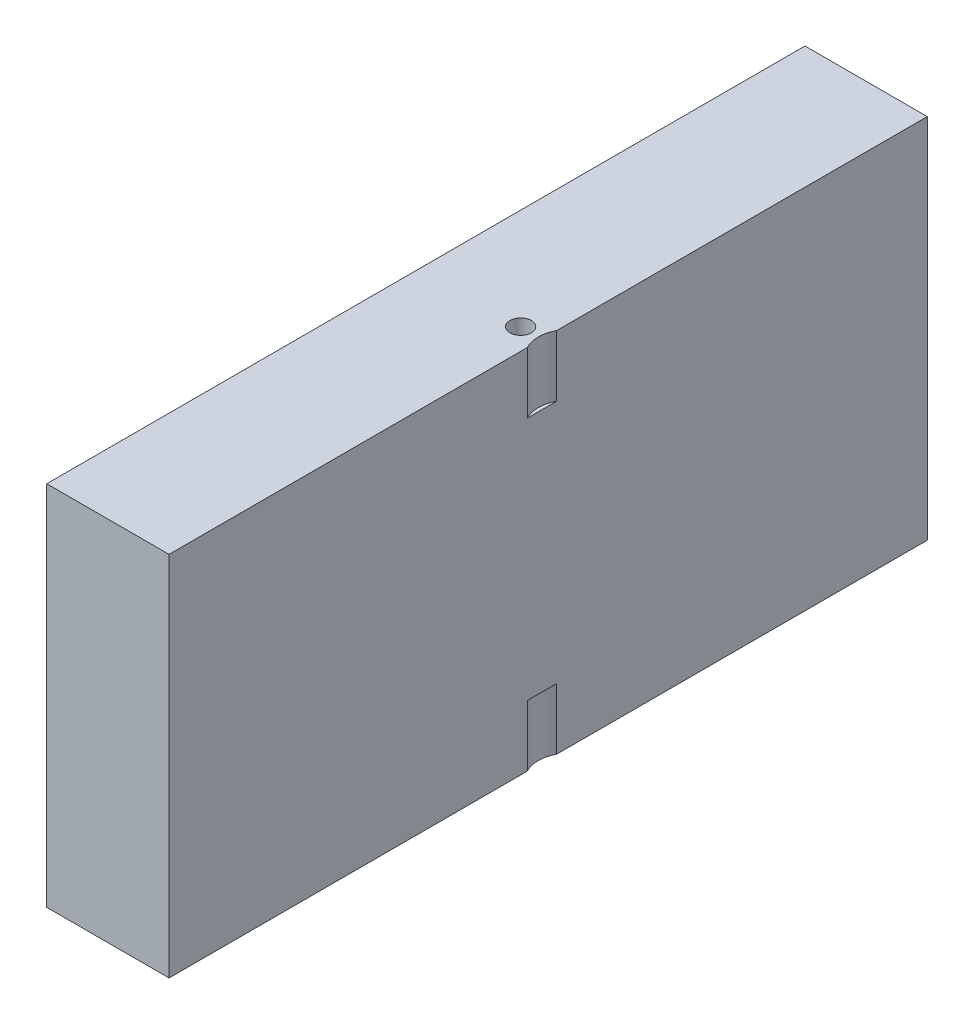
SolidWorks part; units mm, degrees
ref_plane "Front Plane" through (0, 0, 0) normal (0, 0, 1) x (1, 0, 0)
ref_plane "Top Plane" through (0, 0, 0) normal (0, 1, 0) x (1, 0, 0)
ref_plane "Right Plane" through (0, 0, 0) normal (1, 0, 0) x (0, 0, -1)
sketch "Sketch1" plane through (0, 0, 0) normal (0, 0, 1) x (1, 0, 0)
  line L1 (-10, -30) -> (10, -30)
  line L2 (-10, -30) -> (-10, 30)
  line L3 (-10, 30) -> (10, 30)
  line L4 (10, -30) -> (10, 30)
  line L5 (-10, -30) -> (10, 30) construction
  line L6 (-10, 30) -> (10, -30) construction
  point P0 (0, 0)
  dimension "D1" = 60
  dimension "D2" = 20
extrude "Boss-Extrude1" add sketch "Sketch1" along normal mid plane 124
sketch "Sketch2" plane through (0, 30, 0) normal (0, 1, 0) x (1, 0, 0)
  line L0 (-10, -1) -> (14.5, -1) construction
  line L1 (-10, -62) -> (-10, 62) construction
  line L2 (0, 0) -> (-10, 0) construction
  circle A0 centre (14.5, -1) radius 5.1
  dimension "D2" = 10.2
  dimension "D1" = 24.5
  dimension "D3" = 1
extrude "Cut-Extrude1" cut sketch "Sketch2" against normal blind 10
mirror "Mirror1" about plane through (0, 0, 0) normal (0, 1, 0) of "Cut-Extrude1"
sketch "Sketch3" plane through (0, 30, 0) normal (0, 1, 0) x (1, 0, 0)
  line L0 (14.5, -1) -> (6.5, -1) construction
  circle A0 centre (14.5, -1) radius 4
  circle A1 centre (6.5, -1) radius 1.75
  circle A2 centre (14.5, 7) radius 1.75
  circle A3 centre (22.5, -1) radius 1.75
  circle A4 centre (14.5, -9) radius 1.75
  point P5 (14.5, -1)
  point P14 (14.5, -1)
  dimension "D1" = 3.5
  dimension "D2" = 8
  dimension "D4" = 16
  dimension "D3" = 4
extrude "Cut-Extrude2" cut sketch "Sketch3" against normal through all
